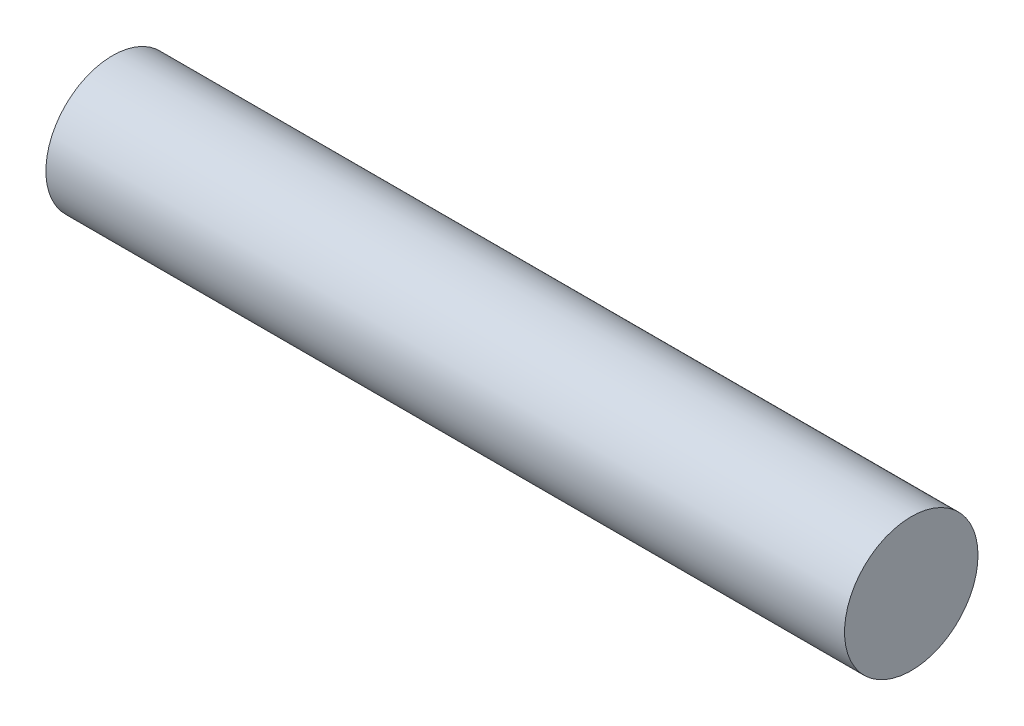
SolidWorks part; units mm, degrees
ref_plane "Front Plane" through (0, 0, 0) normal (0, 0, 1) x (1, 0, 0)
ref_plane "Top Plane" through (0, 0, 0) normal (0, 1, 0) x (1, 0, 0)
ref_plane "Right Plane" through (0, 0, 0) normal (1, 0, 0) x (0, 0, -1)
sketch "Sketch1" plane through (0, 0, 0) normal (1, 0, 0) x (0, 0, -1)
  circle A0 centre (0, 0) radius 8.89
  dimension "D1" = 17.78
extrude "Boss-Extrude1" add sketch "Sketch1" along normal blind 103.2 and the other way blind 3.2
